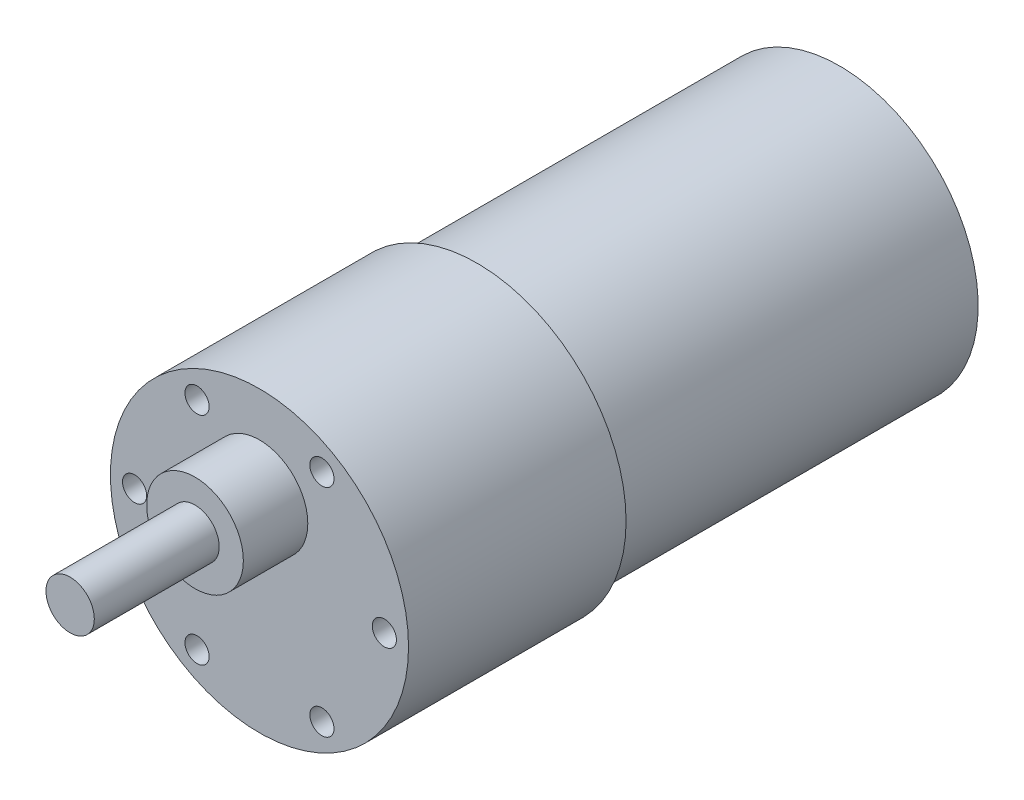
SolidWorks part; units mm, degrees
material "AISI 1015 钢，冷拔 (SS)"
ref_plane "前视基准面" through (0, 0, 0) normal (0, 0, 1) x (1, 0, 0)
ref_plane "上视基准面" through (0, 0, 0) normal (0, 1, 0) x (1, 0, 0)
ref_plane "右视基准面" through (0, 0, 0) normal (1, 0, 0) x (0, 0, -1)
sketch "草图1" plane through (0, 0, 0) normal (0, 0, 1) x (1, 0, 0)
  circle A0 centre (0, 0) radius 17.2
  dimension "D1" = 34.4
extrude "凸台-拉伸1" add sketch "草图1" along normal blind 45
sketch "草图2" plane through (0, 0, 45) normal (0, 0, 1) x (1, 0, 0)
  circle A0 centre (0, 0) radius 18.5
  dimension "D1" = 37
extrude "凸台-拉伸2" add sketch "草图2" along normal blind 27
sketch "草图6" plane through (0, 0, 72) normal (0, 0, 1) x (1, 0, 0)
  circle A0 centre (0, 0) radius 15.5 construction
  circle A1 centre (-15.5, 0) radius 1.5
  circle A2 centre (-7.75, 13.4234) radius 1.5
  circle A3 centre (7.75, 13.4234) radius 1.5
  circle A4 centre (15.5, 0) radius 1.5
  circle A5 centre (7.75, -13.4234) radius 1.5
  circle A6 centre (-7.75, -13.4234) radius 1.5
  point P6 (0, 0)
  point P7 (-0.4552, 7.2133)
  point P17 (0, 0)
  point P19 (-0.4552, 7.2133)
  point P20 (0, 0)
  dimension "D1" = 31
  dimension "D2" = 3
  dimension "D3" = 6
extrude "切除-拉伸1" cut sketch "草图6" against normal blind 10
sketch "草图3" plane through (0, 0, 72) normal (0, 0, 1) x (1, 0, 0)
  line L0 (15.5, 0) -> (-15.5, 0) construction
  circle A0 centre (0, 7) radius 6
  circle A1 centre (-15.5, 0) radius 1.5 construction
  circle A2 centre (15.5, 0) radius 1.5 construction
  circle A3 centre (-15.5, 0) radius 1.5 construction
  circle A4 centre (15.5, 0) radius 1.5 construction
  point P3 (0, 0)
  point P4 (0, 6.928)
  dimension "D1" = 12
  dimension "D2" = 7
extrude "凸台-拉伸3" add sketch "草图3" along normal blind 8
sketch "草图4" plane through (0, 0, 80) normal (0, 0, 1) x (1, 0, 0)
  circle A0 centre (0, 7) radius 3
  point P3 (0, 0)
  point P4 (-0.4552, 7.2133)
  dimension "D1" = 6
extrude "凸台-拉伸4" add sketch "草图4" along normal blind 15.5
